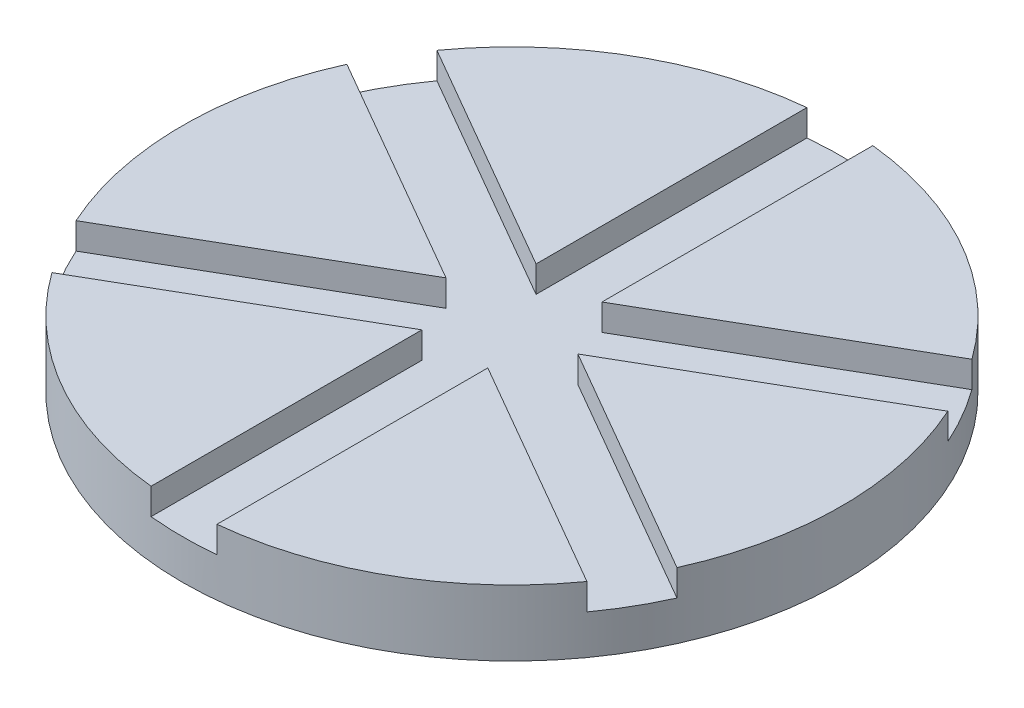
SolidWorks part; units mm, degrees
ref_plane "Front Plane" through (0, 0, 0) normal (0, 0, 1) x (1, 0, 0)
ref_plane "Top Plane" through (0, 0, 0) normal (0, 1, 0) x (1, 0, 0)
ref_plane "Right Plane" through (0, 0, 0) normal (1, 0, 0) x (0, 0, -1)
sketch "Sketch1" plane through (0, 0, 0) normal (0, 1, 0) x (1, 0, 0)
  circle A0 centre (0, 0) radius 127
  dimension "D1" = 254
extrude "Boss-Extrude1" add sketch "Sketch1" along normal blind 25.4
sketch "Sketch2" plane through (0, 25.4, 0) normal (0, 1, 0) x (1, 0, 0)
  line L0 (0, -127) -> (0, 127) construction
  line L1 (109.9852, 63.5) -> (-109.9852, -63.5) construction
  line L2 (-109.9852, 63.5) -> (109.9852, -63.5) construction
  line L3 (12.7, -127) -> (12.7, -21.997)
  line L4 (-12.7, -127) -> (-12.7, -21.997)
  line L5 (-116.3352, 52.5015) -> (-25.4, 0)
  line L6 (-103.6352, 74.4985) -> (-12.7, 21.997)
  line L7 (103.6352, 74.4985) -> (12.7, 21.997)
  line L8 (116.3352, 52.5015) -> (25.4, 0)
  line L9 (-25.4, 0) -> (-116.3352, -52.5015)
  line L10 (103.6352, 74.4985) -> (-116.3352, -52.5015) construction
  line L11 (-12.7, 21.997) -> (-12.7, 127)
  line L12 (-12.7, -127) -> (-12.7, 127) construction
  line L13 (25.4, 0) -> (116.3352, -52.5015)
  line L14 (-103.6352, 74.4985) -> (116.3352, -52.5015) construction
  line L15 (12.7, 21.997) -> (12.7, 127)
  line L16 (12.7, -127) -> (12.7, 127) construction
  line L17 (-12.7, -21.997) -> (-103.6352, -74.4985)
  line L18 (116.3352, 52.5015) -> (-103.6352, -74.4985) construction
  line L19 (-103.6352, -74.4985) -> (-133.4495, -77.8465)
  line L20 (-133.4495, -77.8465) -> (-116.3352, -52.5015)
  line L21 (-116.3352, 52.5015) -> (-124.8924, 78.3793)
  line L22 (-124.8924, 78.3793) -> (-103.6352, 74.4985)
  line L23 (-12.7, 127) -> (0, 157.9845)
  line L24 (0, 157.9845) -> (12.7, 127)
  line L25 (103.6352, 74.4985) -> (130.311, 77.494)
  line L26 (130.311, 77.494) -> (116.3352, 52.5015)
  line L27 (116.3352, -52.5015) -> (138.3323, -74.4985)
  line L28 (138.3323, -74.4985) -> (103.6352, -74.4985)
  line L29 (12.7, -127) -> (12.7, -156.1367)
  line L30 (12.7, -156.1367) -> (-12.7, -127)
  line L31 (12.7, -21.997) -> (103.6352, -74.4985)
  line L32 (-116.3352, 52.5015) -> (103.6352, -74.4985) construction
  circle A0 centre (0, 0) radius 127 construction
  point P12 (0, 0)
  dimension "D2" = 12.7
  dimension "D3" = 12.7
  dimension "D4" = 12.7
  dimension "D5" = 12.7
  dimension "D6" = 12.7
  dimension "D7" = 12.7
  dimension "D1" = 3
extrude "Cut-Extrude1" cut sketch "Sketch2" against normal blind 10.16
sketch "Sketch3" plane through (0, 0, 0) normal (0, -1, 0) x (-1, 0, 0)
  circle A0 centre (0, 0) radius 12.7
  dimension "D1" = 25.4
extrude "Boss-Extrude2" add sketch "Sketch3" along normal blind 38.1
